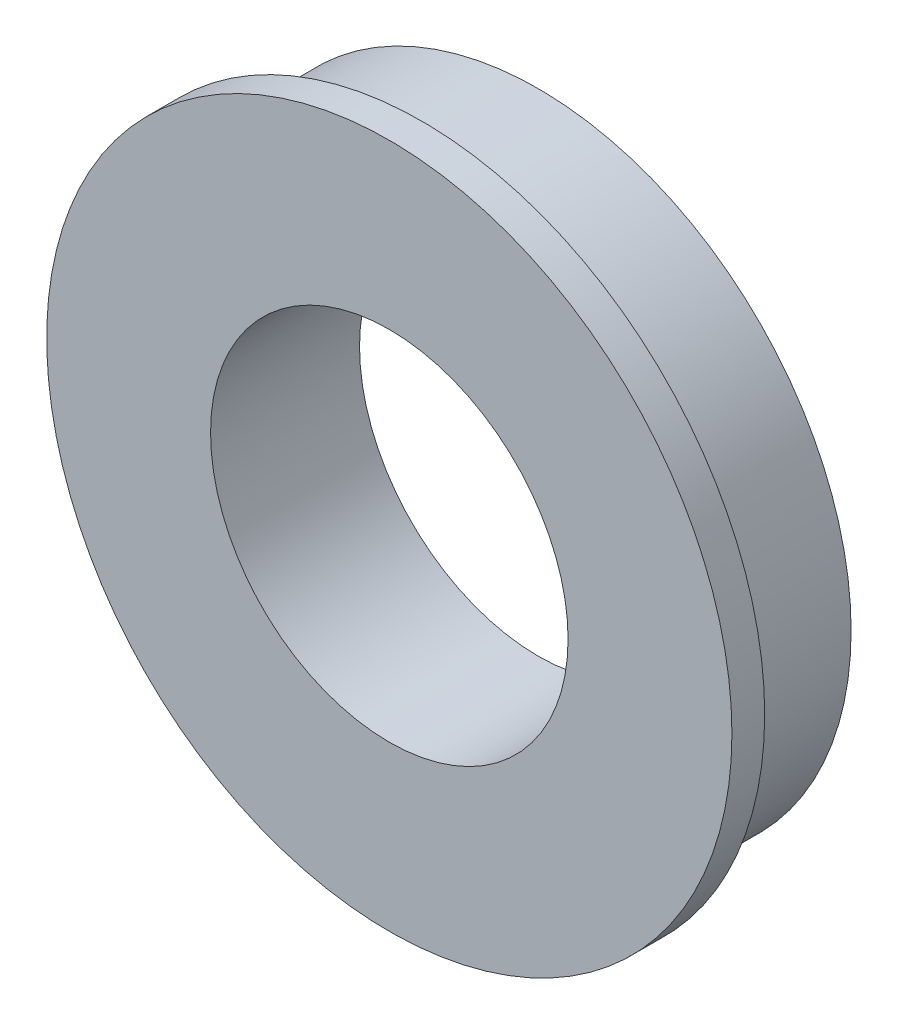
SolidWorks part; units mm, degrees
material "Plain Carbon Steel"
ref_plane "Front Plane" through (0, 0, 0) normal (0, 0, 1) x (1, 0, 0)
ref_plane "Top Plane" through (0, 0, 0) normal (0, 1, 0) x (1, 0, 0)
ref_plane "Right Plane" through (0, 0, 0) normal (1, 0, 0) x (0, 0, -1)
sketch "Sketch1" plane through (0, 0, 0) normal (1, 0, 0) x (0, 0, -1)
  line L0 (0, 0) -> (5, 0) construction
  line L1 (0, 6) -> (5, 6)
  line L2 (5, 6) -> (5, 10.5)
  line L3 (5, 10.5) -> (1.1, 10.5)
  line L4 (1.1, 10.5) -> (1.1, 11.5)
  line L5 (1.1, 11.5) -> (0, 11.5)
  line L6 (0, 11.5) -> (0, 6)
  dimension "D1" = 12
  dimension "D2" = 21
  dimension "D3" = 5
  dimension "D4" = 1.1
  dimension "D5" = 23
revolve "Revolve1" add sketch "Sketch1" angle 360 about L0
